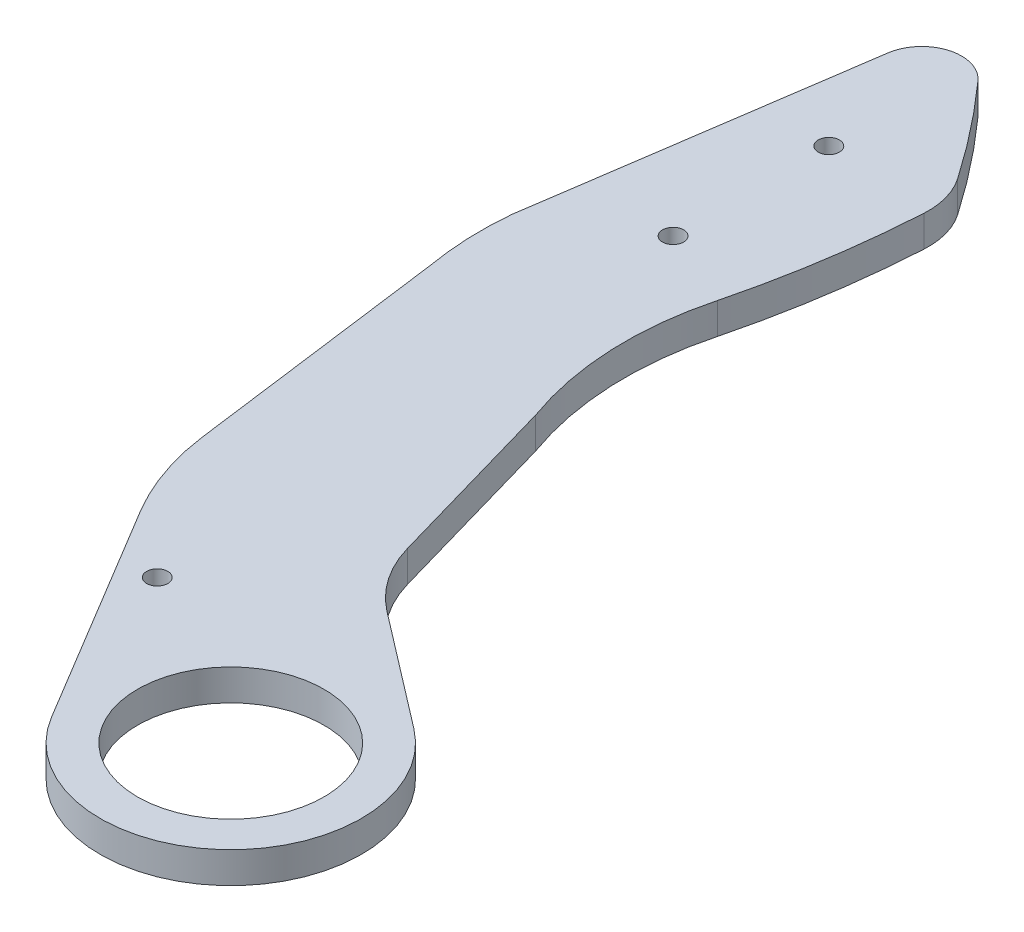
SolidWorks part; units mm, degrees
ref_plane "Front Plane" through (0, 0, 0) normal (0, 0, 1) x (1, 0, 0)
ref_plane "Top Plane" through (0, 0, 0) normal (0, 1, 0) x (1, 0, 0)
ref_plane "Right Plane" through (0, 0, 0) normal (1, 0, 0) x (0, 0, -1)
sketch "Sketch1" plane through (0, 0, 0) normal (0, 1, 0) x (1, 0, 0)
  line L42 (12.7565, 16.65) -> (-5.8126, 30.8768)
  line L43 (-12.8764, 41.2474) -> (-21.1346, 70.0884)
  line L44 (-43.1946, 148.7152) -> (-50.9327, 96.0562)
  line L45 (-50.3835, 82.3644) -> (-44.8247, 40.2908)
  line L46 (-39.4529, 24.9234) -> (-17.9775, -10.8056)
  arc A148 (-22.4566, 100.5997) -> (-21.1346, 70.0884) centre (26.9938, 87.458) ccw
  arc A149 (-22.4566, 100.5997) -> (-18.0206, 129.2968) centre (-171.2572, 138.2924) ccw
  arc A150 (-18.0206, 129.2968) -> (-20.1164, 136.8055) centre (-30, 130) ccw
  arc A151 (-20.1164, 136.8055) -> (-32.0981, 152.0476) centre (-146.5445, 49.7519) ccw
  arc A152 (-32.0981, 152.0476) -> (-43.1946, 148.7152) centre (-36.8667, 147.7853) ccw
  arc A153 (-50.9327, 96.0562) -> (-50.3835, 82.3644) centre (0.0072, 91.2427) ccw
  circle A154 centre (0, 0) radius 14.975
  arc A155 (12.7565, 16.65) -> (-17.9775, -10.8056) centre (0, 0) cw
  arc A156 (-5.8126, 30.8768) -> (-12.8764, 41.2474) centre (6.3509, 46.7529) cw
  arc A157 (-44.8247, 40.2908) -> (-39.4529, 24.9234) centre (-5.1693, 45.5301) ccw
  circle A158 centre (-28.9308, 17.1233) radius 1.7
  point P7 (-11.0576, 34.8953)
  point P11 (-43.7358, 32.0489)
  dimension "D3" = 12
  dimension "D4" = 29.95
  dimension "D5" = 6
  dimension "D8" = 20
  dimension "D10" = 40
  dimension "D11" = 3.4
  dimension "D1" = 130
  dimension "D2" = 30
  dimension "D6" = 50
  dimension "D7" = 30
  dimension "D9" = 30
  dimension "D12" = 5
  dimension "D13" = 30
extrude "Boss-Extrude2" add sketch "Sketch1" along normal blind 5
sketch "Sketch2" plane through (0, 5, 0) normal (0, 1, 0) x (1, 0, 0)
  line L0 (12.7565, 16.65) -> (-5.8126, 30.8768) construction
  point P0 (11.1186, 17.9049)
sketch "Sketch3" plane through (0, 5, 0) normal (0, 1, 0) x (1, 0, 0)
  circle A0 centre (-35, 131) radius 1.7
  circle A1 centre (-35, 106) radius 1.7
  point P4 (0, 0)
  point P5 (0, 0)
  point P8 (-4.07, 92.9791)
  dimension "D1" = 3.4
  dimension "D2" = 3.4
  dimension "D3" = 25
  dimension "D4" = 106
  dimension "D5" = 35
extrude "Cut-Extrude1" cut sketch "Sketch3" against normal up to next
